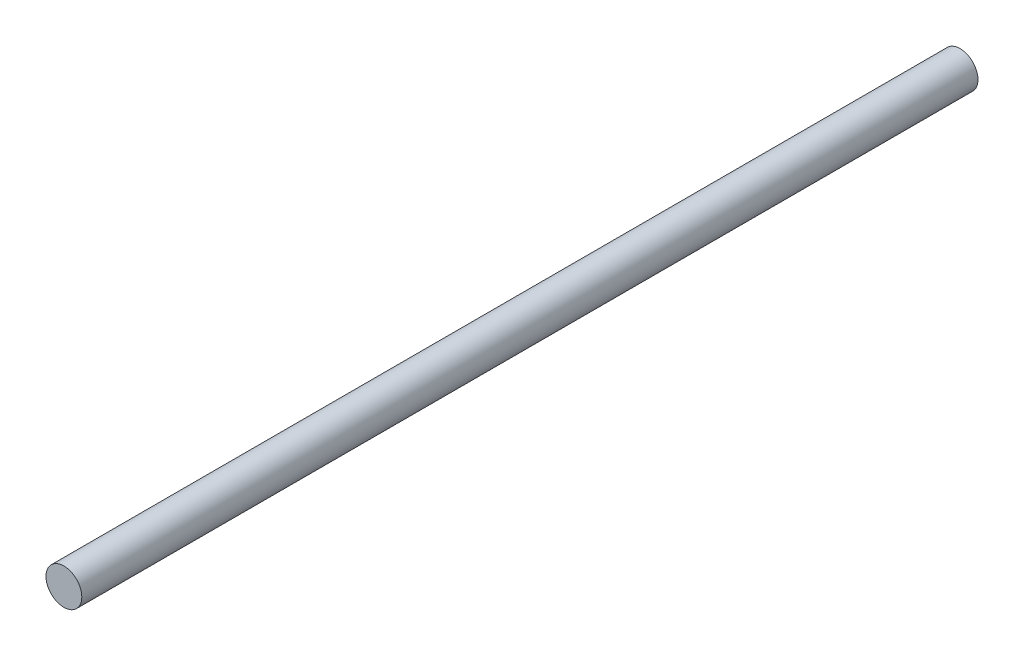
SolidWorks part; units mm, degrees
ref_plane "Plan de face" through (0, 0, 0) normal (0, 0, 1) x (1, 0, 0)
ref_plane "Plan de dessus" through (0, 0, 0) normal (0, 1, 0) x (1, 0, 0)
ref_plane "Plan de droite" through (0, 0, 0) normal (1, 0, 0) x (0, 0, -1)
sketch "Esquisse1" plane through (0, 0, 0) normal (0, 0, 1) x (1, 0, 0)
  circle A0 centre (0, 0) radius 4
  dimension "D1" = 8
extrude "Boss.-Extru.1" add sketch "Esquisse1" along normal blind 200
